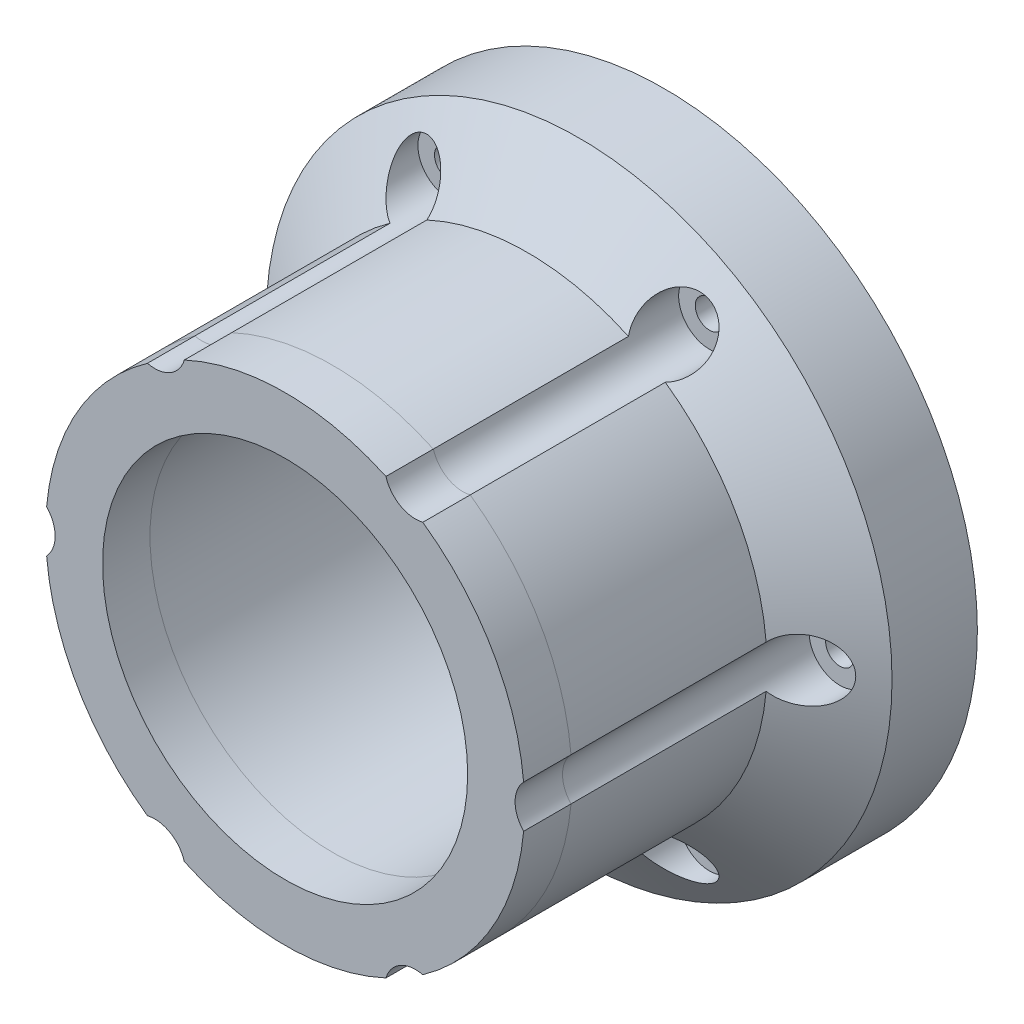
SolidWorks part; units mm, degrees
other "Final-Part"
other "Printing-Shim"
material "Acrylic (Medium-high impact)"
ref_plane "Front Plane" through (0, 0, 0) normal (0, 0, 1) x (1, 0, 0)
ref_plane "Top Plane" through (0, 0, 0) normal (0, 1, 0) x (1, 0, 0)
ref_plane "Right Plane" through (0, 0, 0) normal (1, 0, 0) x (0, 0, -1)
sketch "Sketch1" plane through (0, 0, 0) normal (0, 0, 1) x (1, 0, 0)
  line L0 (0, 0) -> (-33, 0) construction
  circle A0 centre (0, 0) radius 33
  circle A1 centre (0, 0) radius 19.25
  circle A2 centre (-27.5, 0) radius 1.5
  circle A3 centre (-13.75, 23.8157) radius 1.5
  circle A4 centre (13.75, 23.8157) radius 1.5
  circle A5 centre (27.5, 0) radius 1.5
  circle A6 centre (13.75, -23.8157) radius 1.5
  circle A7 centre (-13.75, -23.8157) radius 1.5
  point P17 (0, 0)
  dimension "D1" = 38.5
  dimension "D2" = 66
  dimension "D3" = 3
  dimension "D4" = 5.5
  dimension "D5" = 6
extrude "Boss-Extrude1" add sketch "Sketch1" along normal blind 35
sketch "Sketch6" plane through (0, 0, 0) normal (1, 0, 0) x (0, 0, -1)
  line L0 (0, -19.25) -> (0, 19.25) construction
  line L1 (0, -19.25) -> (0, 19.25) construction
  line L4 (-35, 33) -> (-9, 33)
  line L5 (0, 33) -> (-35, 33) construction
  line L7 (-14.4266, 19.25) -> (0, 19.25) construction
  line L8 (0, 19.25) -> (0, 33) construction
  line L9 (0, 33) -> (-9, 33) construction
  line L10 (-14.4266, 19.25) -> (-14.4266, 33) construction
  line L11 (0, 0) -> (-35, 0) construction
  line L12 (-35, 0) -> (-35, 19.25) construction
  line L13 (-14.4266, 19.25) -> (-35, 19.25) construction
  line L14 (-14.4266, 25.25) -> (-35, 25.25)
  line L15 (-14.4266, 25.25) -> (-9, 33)
  line L16 (-35, 33) -> (-35, 25.25)
  line L17 (-35, 25.25) -> (-35, 19.25) construction
  dimension "D1" = 9
  dimension "D2" = 35
  dimension "D3" = 6
revolve "Cut-Revolve1" cut sketch "Sketch6" angle 360 about L11
sketch "Sketch4" plane through (0, 0, 0) normal (0, 0, -1) x (-1, 0, 0)
  circle A2 centre (0, 0) radius 22.25
  circle A3 centre (0, 0) radius 22.25
  circle A5 centre (0, 0) radius 30
  circle A6 centre (0, 0) radius 30
  dimension "D1" = 3
  dimension "D2" = 3
extrude "Cut-Extrude1" cut sketch "Sketch4" against normal blind 5
sketch "Sketch5" plane through (0, 0, 35) normal (0, 0, 1) x (1, 0, 0)
  circle A12 centre (-13.75, 23.8157) radius 3.25
  circle A13 centre (-27.5, 0) radius 3.25
  circle A14 centre (-13.75, -23.8157) radius 3.25
  circle A15 centre (13.75, -23.8157) radius 3.25
  circle A16 centre (27.5, 0) radius 3.25
  circle A17 centre (13.75, 23.8157) radius 3.25
  circle A19 centre (13.75, 23.8157) radius 1.5 construction
  circle A20 centre (-13.75, 23.8157) radius 1.5 construction
  circle A21 centre (-27.5, 0) radius 1.5 construction
  circle A22 centre (27.5, 0) radius 1.5 construction
  circle A23 centre (13.75, -23.8157) radius 1.5 construction
  circle A24 centre (-13.75, -23.8157) radius 1.5 construction
  circle A25 centre (13.75, 23.8157) radius 1.5
  circle A26 centre (-13.75, 23.8157) radius 1.5
  circle A27 centre (-27.5, 0) radius 1.5
  circle A28 centre (27.5, 0) radius 1.5
  circle A29 centre (13.75, -23.8157) radius 1.5
  circle A30 centre (-13.75, -23.8157) radius 1.5
  dimension "D1" = 6.5
extrude "Cut-Extrude2" cut sketch "Sketch5" against normal blind 26
sketch "Sketch7" plane through (0, 0, 35) normal (0, 0, 1) x (1, 0, 0)
  circle A0 centre (0, 0) radius 19.25 construction
  circle A1 centre (0, 0) radius 19.25
  arc A12 (10.6308, 22.903) -> (14.5192, 20.658) centre (13.75, 23.8157) ccw
  arc A13 (10.6308, 22.903) -> (-10.6308, 22.903) centre (0, 0) ccw
  arc A14 (-14.5192, 20.658) -> (-10.6308, 22.903) centre (-13.75, 23.8157) ccw
  arc A15 (-14.5192, 20.658) -> (-25.15, 2.245) centre (0, 0) ccw
  arc A16 (-25.15, -2.245) -> (-25.15, 2.245) centre (-27.5, 0) ccw
  arc A17 (-25.15, -2.245) -> (-14.5192, -20.658) centre (0, 0) ccw
  arc A18 (-10.6308, -22.903) -> (-14.5192, -20.658) centre (-13.75, -23.8157) ccw
  arc A19 (-10.6308, -22.903) -> (10.6308, -22.903) centre (0, 0) ccw
  arc A20 (14.5192, -20.658) -> (10.6308, -22.903) centre (13.75, -23.8157) ccw
  arc A21 (14.5192, -20.658) -> (25.15, -2.245) centre (0, 0) ccw
  arc A22 (25.15, 2.245) -> (25.15, -2.245) centre (27.5, 0) ccw
  arc A23 (25.15, 2.245) -> (14.5192, 20.658) centre (0, 0) ccw
  arc A24 (10.6308, 22.903) -> (14.5192, 20.658) centre (13.75, 23.8157) ccw
  arc A25 (10.6308, 22.903) -> (-10.6308, 22.903) centre (0, 0) ccw
  arc A26 (-14.5192, 20.658) -> (-10.6308, 22.903) centre (-13.75, 23.8157) ccw
  arc A27 (-14.5192, 20.658) -> (-25.15, 2.245) centre (0, 0) ccw
  arc A28 (-25.15, -2.245) -> (-25.15, 2.245) centre (-27.5, 0) ccw
  arc A29 (-25.15, -2.245) -> (-14.5192, -20.658) centre (0, 0) ccw
  arc A30 (-10.6308, -22.903) -> (-14.5192, -20.658) centre (-13.75, -23.8157) ccw
  arc A31 (-10.6308, -22.903) -> (10.6308, -22.903) centre (0, 0) ccw
  arc A32 (14.5192, -20.658) -> (10.6308, -22.903) centre (13.75, -23.8157) ccw
  arc A33 (14.5192, -20.658) -> (25.15, -2.245) centre (0, 0) ccw
  arc A34 (25.15, 2.245) -> (25.15, -2.245) centre (27.5, 0) ccw
  arc A35 (25.15, 2.245) -> (14.5192, 20.658) centre (0, 0) ccw
  dimension "D1" = 0
extrude "Shim-Feature" add sketch "Sketch7" along normal blind 5 separate body
sketch "Sketch9" plane through (0, 0, 0) normal (0, 0, -1) x (-1, 0, 0)
  line L0 (0, 0) -> (0, -33) construction
  line L1 (-3.5, -33) -> (3.5, -33)
  line L3 (3.5, -33) -> (3.5, -26.1305)
  line L4 (3.5, -26.1305) -> (-3.5, -26.1305)
  line L5 (-3.5, -26.1305) -> (-3.5, -33)
  circle A0 centre (0, 0) radius 33 construction
  point P8 (0, -33)
  dimension "D1" = 7
extrude "Cut-Extrude5" cut sketch "Sketch9" against normal up to surface (5 mm away) up to face at (-29, 0, 5)
